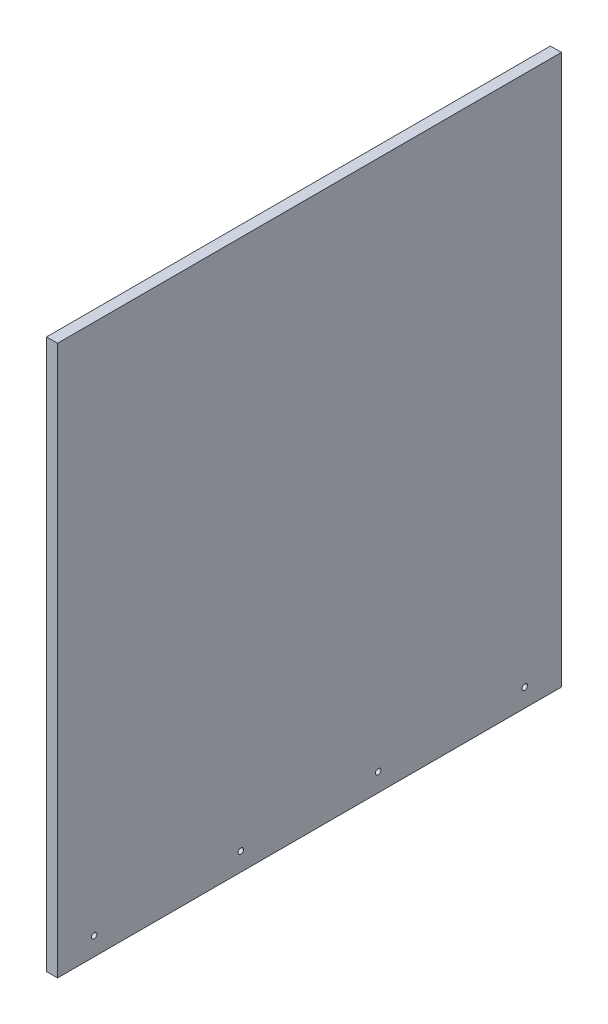
SolidWorks part; units mm, degrees
ref_plane "Front Plane" through (0, 0, 0) normal (0, 0, 1) x (1, 0, 0)
ref_plane "Top Plane" through (0, 0, 0) normal (0, 1, 0) x (1, 0, 0)
ref_plane "Right Plane" through (0, 0, 0) normal (1, 0, 0) x (0, 0, -1)
sketch "Sketch1" plane through (0, 0, 0) normal (0, 0, 1) x (1, 0, 0)
  line L0 (-145.7296, 0) -> (157.1806, 0) construction
  line L1 (-3, 150) -> (3, 150)
  line L2 (-3, 150) -> (-3, -150)
  line L3 (-3, -150) -> (3, -150)
  line L4 (3, 150) -> (3, -150)
  line L5 (0, 57.743) -> (0, -95.443) construction
  dimension "D1" = 6
  dimension "D2" = 300
extrude "Boss-Extrude1" add sketch "Sketch1" along normal mid plane 275
sketch "Sketch2" plane through (0, 0, 0) normal (1, 0, 0) x (0, 0, -1)
  line L0 (-137.5, -150) -> (137.5, -150) construction
  line L1 (-137.5, -150) -> (-137.5, 150) construction
  line L2 (0, 3.3) -> (0, -3.3) construction
  circle A0 centre (-117.5, -140) radius 1.5
  circle A1 centre (-37.5, -140) radius 1.5
  circle A2 centre (37.5, -140) radius 1.5
  circle A3 centre (117.5, -140) radius 1.5
  dimension "D1" = 3
  dimension "D4" = 3
  dimension "D2" = 10
  dimension "D3" = 20
  dimension "D5" = 10
  dimension "D6" = 80
extrude "Cut-Extrude1" cut sketch "Sketch2" along normal through all both and the other way through all
